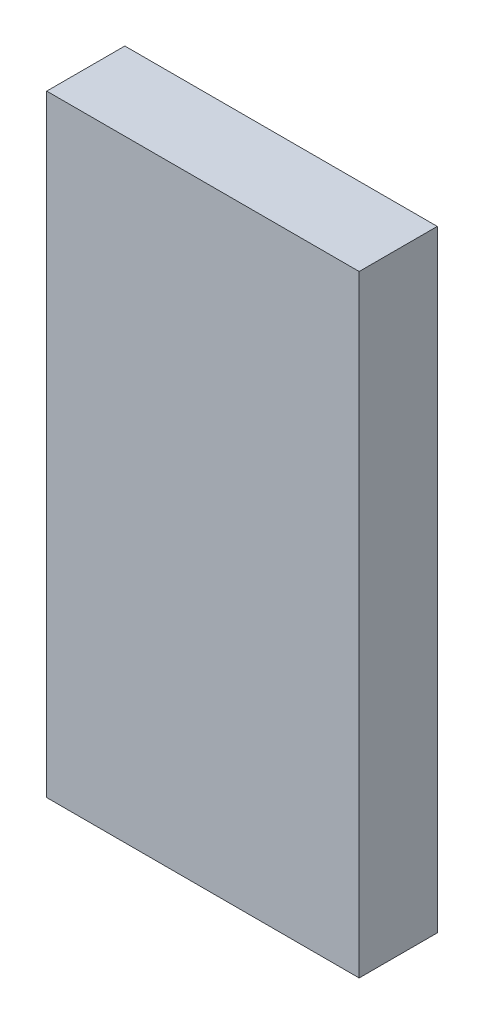
SolidWorks part; units mm, degrees
ref_plane "Front" through (0, 0, 0) normal (0, 0, 1) x (1, 0, 0)
ref_plane "Top" through (0, 0, 0) normal (0, 1, 0) x (1, 0, 0)
ref_plane "Right" through (0, 0, 0) normal (1, 0, 0) x (0, 0, -1)
sketch "Esboço1" plane through (0, 0, 0) normal (0, 0, 1) x (1, 0, 0)
  line L1 (-15.2778, 14.4593) -> (-3.2778, 14.4593)
  line L2 (-15.2778, 14.4593) -> (-15.2778, -9.0407)
  line L3 (-15.2778, -9.0407) -> (-3.2778, -9.0407)
  line L4 (-3.2778, 14.4593) -> (-3.2778, -9.0407)
  line L5 (-15.2778, 14.4593) -> (-3.2778, -9.0407) construction
  line L6 (-15.2778, -9.0407) -> (-3.2778, 14.4593) construction
  point P0 (-9.2778, 2.7093)
  dimension "D1" = 23.5
  dimension "D2" = 12
extrude "Ressalto-extrusão1" add sketch "Esboço1" along normal blind 3
